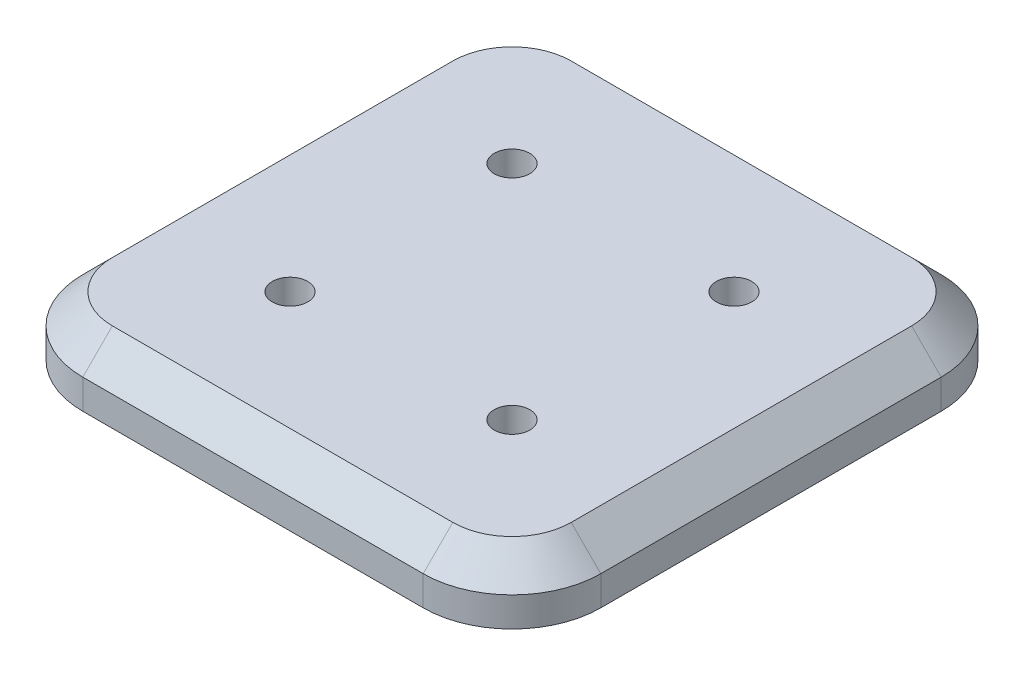
SolidWorks part; units mm, degrees
ref_plane "前基準面" through (0, 0, 0) normal (0, 0, 1) x (1, 0, 0)
ref_plane "上基準面" through (0, 0, 0) normal (0, 1, 0) x (1, 0, 0)
ref_plane "右基準面" through (0, 0, 0) normal (1, 0, 0) x (0, 0, -1)
ref_plane "平面1"
sketch "草圖1" plane through (0, 0, 0) normal (0, 1, 0) x (-1, 0, 0)
  line L0 (87.5, -87.5) -> (-87.5, -87.5)
  line L1 (-87.5, -87.5) -> (-87.5, 87.5)
  line L2 (-87.5, 87.5) -> (87.5, 87.5)
  line L3 (87.5, 87.5) -> (87.5, -87.5)
  dimension "D1" = 175
  dimension "D2" = 175
extrude "擠出1" add sketch "草圖1" along normal blind 20
fillet "圓角1" radius 30 4 edges at (87.5, 10, -87.5) (-87.5, 10, -87.5) (-87.5, 10, 87.5) (87.5, 10, 87.5)
chamfer "倒角1" distance 10 distance2 10 8 edges at (0, 20, 87.5) (78.7132, 20, 78.7132) (87.5, 20, 0) (78.7132, 20, -78.7132) (0, 20, -87.5) (-78.7132, 20, -78.7132) (-87.5, 20, 0) (-78.7132, 20, 78.7132)
hole_wizard "孔1" positions "草圖3" profile "草圖2" legacy
sketch "草圖3" plane through (0, 0, 0) normal (0, -1, 0) x (-1, 0, 0)
  point P1 (62.5, -62.5)
  point P2 (-62.5, -62.5)
  point P3 (-62.5, 62.5)
  point P4 (62.5, 62.5)
sketch "草圖2" plane through (-62.5, 0, 62.5) normal (1, 0, 0) x (0, 0, -1)
  line L0 (0, 0) -> (0, 13.6052)
  line L1 (0, 13.6052) -> (6, 10)
  line L2 (6, 10) -> (6, 0)
  line L4 (6, 0) -> (0, 0)
  line L6 (0, 13.6052) -> (-6, 10) construction
  line L7 (0, -4.2442) -> (0, 117.3081) construction
  dimension "直徑" = 12
  dimension "深度" = 10
  dimension "導頭角度" = 118
hole_wizard "孔2" positions "草圖5" profile "草圖4" legacy
sketch "草圖5" plane through (0, 20, 0) normal (0, 1, 0) x (1, 0, 0)
  point P1 (-37.5, 37.5)
  point P2 (-37.5, -37.5)
  point P3 (37.5, -37.5)
  point P4 (37.5, 37.5)
sketch "草圖4" plane through (-37.5, 20, -37.5) normal (1, 0, 0) x (0, 0, 1)
  line L0 (0, 0) -> (0, 13.6052)
  line L1 (0, 13.6052) -> (6, 10)
  line L2 (6, 10) -> (6, 0)
  line L4 (6, 0) -> (0, 0)
  line L6 (0, 13.6052) -> (-6, 10) construction
  line L7 (0, -4.2442) -> (0, 117.3081) construction
  dimension "直徑" = 12
  dimension "深度" = 10
  dimension "導頭角度" = 118
